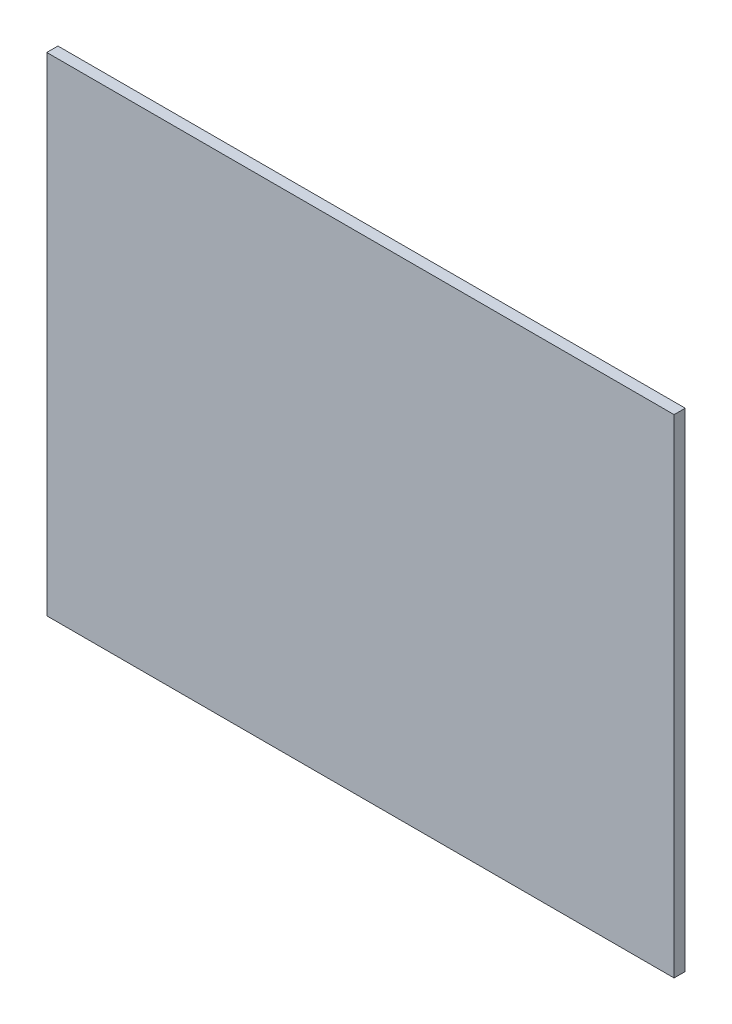
SolidWorks part; units mm, degrees
ref_plane "Front Plane" through (0, 0, 0) normal (0, 0, 1) x (1, 0, 0)
ref_plane "Top Plane" through (0, 0, 0) normal (0, 1, 0) x (1, 0, 0)
ref_plane "Right Plane" through (0, 0, 0) normal (1, 0, 0) x (0, 0, -1)
sketch "Sketch1" plane through (0, 0, 0) normal (0, 0, 1) x (1, 0, 0)
  line L0 (22.5, -125) -> (22.5, -5) construction
  line L1 (-217.5, -135) -> (12.5, -135) construction
  line L2 (-157.5, -125) -> (-157.5, -5) construction
  line L3 (-147.5, 5) -> (12.5, 5) construction
  line L4 (22.5, -125) -> (22.5, -5)
  line L5 (-217.5, -135) -> (12.5, -135)
  line L6 (-157.5, -125) -> (-157.5, -5)
  line L7 (-147.5, 5) -> (12.5, 5)
  line L9 (-157.5, 5) -> (22.5, 5)
  line L10 (-157.5, 5) -> (-157.5, -135)
  line L11 (-157.5, -135) -> (22.5, -135)
  line L12 (22.5, 5) -> (22.5, -135)
  point P8 (-157.5, -44.9597)
extrude "Boss-Extrude1" add sketch "Sketch1" along normal blind 3.2 contours L12 L9 L7 L10 L6 L5 L11 L4
